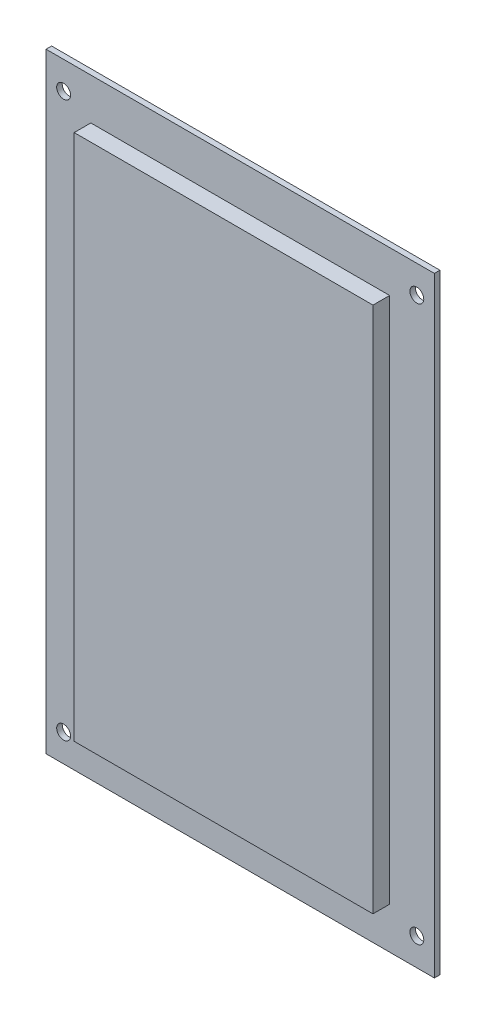
SolidWorks part; units mm, degrees
ref_plane "Front Plane" through (0, 0, 0) normal (0, 0, 1) x (1, 0, 0)
ref_plane "Top Plane" through (0, 0, 0) normal (0, 1, 0) x (1, 0, 0)
ref_plane "Right Plane" through (0, 0, 0) normal (1, 0, 0) x (0, 0, -1)
sketch "Sketch2" plane through (0, 0, 0) normal (0, 0, 1) x (1, 0, 0)
  line L0 (-20.017, 37.185) -> (33.843, 37.185) construction
  line L1 (-20.017, 43.585) -> (33.843, 43.585)
  line L2 (-20.017, 43.585) -> (-20.017, -51.455)
  line L3 (-20.017, -51.455) -> (33.843, -51.455)
  line L4 (33.843, 43.585) -> (33.843, -51.455)
  line L5 (-20.017, -41.055) -> (33.843, -41.055) construction
  line L6 (6.913, 43.585) -> (6.913, -51.455) construction
  dimension "D1" = 95.04
  dimension "D2" = 53.86
  dimension "D3" = 6.4
  dimension "D4" = 10.4
extrude "Boss-Extrude1" add sketch "Sketch2" along normal blind 3
sketch "Sketch3" plane through (0, 0, 0) normal (0, 0, -1) x (-1, 0, 0)
  line L0 (-6.913, -51.455) -> (-6.913, 43.585) construction
  line L1 (20.017, -51.455) -> (-33.843, -51.455) construction
  line L2 (-33.843, 43.585) -> (20.017, 43.585) construction
  line L3 (-33.843, -3.935) -> (20.017, -3.935) construction
  line L4 (-33.843, -51.455) -> (-33.843, 43.585) construction
  line L5 (20.017, 43.585) -> (20.017, -51.455) construction
  line L7 (-41.913, 51.065) -> (28.087, 51.065)
  line L8 (-41.913, 51.065) -> (-41.913, -58.935)
  line L9 (-41.913, -58.935) -> (28.087, -58.935)
  line L10 (28.087, 51.065) -> (28.087, -58.935)
  line L11 (-41.913, 51.065) -> (28.087, -58.935) construction
  line L12 (-41.913, -58.935) -> (28.087, 51.065) construction
  circle A0 centre (24.9229, 46.0929) radius 1.25
  circle A1 centre (24.9229, -53.9629) radius 1.25
  circle A2 centre (-38.7489, 46.0929) radius 1.25
  circle A3 centre (-38.7489, -53.9629) radius 1.25
  point P12 (-6.913, -3.935)
  point P21 (0, 0)
  point P26 (24.9229, 46.0929)
  dimension "D1" = 2.5
  dimension "D2" = 110
  dimension "D3" = 70
extrude "Boss-Extrude2" add sketch "Sketch3" along normal blind 1
